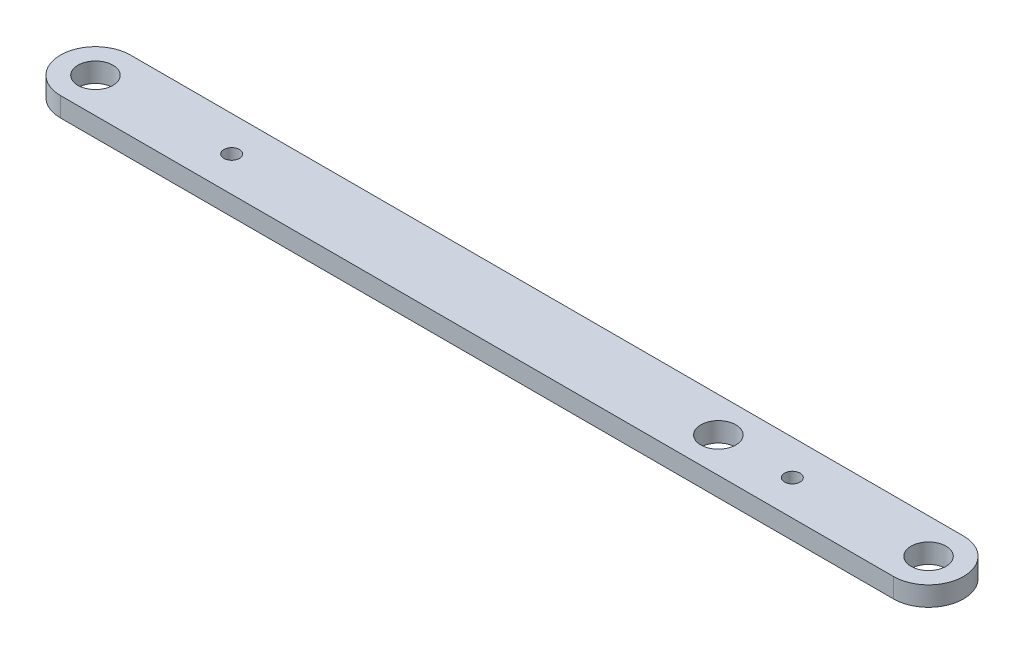
SolidWorks part; units mm, degrees
ref_plane "前视基准面" through (0, 0, 0) normal (0, 0, 1) x (1, 0, 0)
ref_plane "上视基准面" through (0, 0, 0) normal (0, 1, 0) x (1, 0, 0)
ref_plane "右视基准面" through (0, 0, 0) normal (1, 0, 0) x (0, 0, -1)
sketch "草图1" plane through (0, 0, 0) normal (0, 1, 0) x (1, 0, 0)
  line L0 (-140.6097, 23.4238) -> (73.3903, 23.4238)
  line L5 (73.3903, 5.4238) -> (-140.6097, 5.4238)
  arc A0 (-140.6097, 23.4238) -> (-140.6097, 5.4238) centre (-140.6097, 14.4238) ccw
  arc A1 (73.3903, 5.4238) -> (73.3903, 23.4238) centre (73.3903, 14.4238) ccw
  circle A2 centre (-140.6097, 14.4238) radius 4.5
  circle A3 centre (73.3903, 14.4238) radius 4.5
  circle A4 centre (38.3903, 14.4238) radius 2
  circle A5 centre (19.3903, 14.4238) radius 4.5
  circle A7 centre (-105.6097, 14.4238) radius 2
  dimension "D5" = 35
  dimension "D1" = 214
  dimension "D3" = 9
  dimension "D6" = 19
  dimension "D7" = 144
extrude "凸台-拉伸1" add sketch "草图1" along normal blind 5
